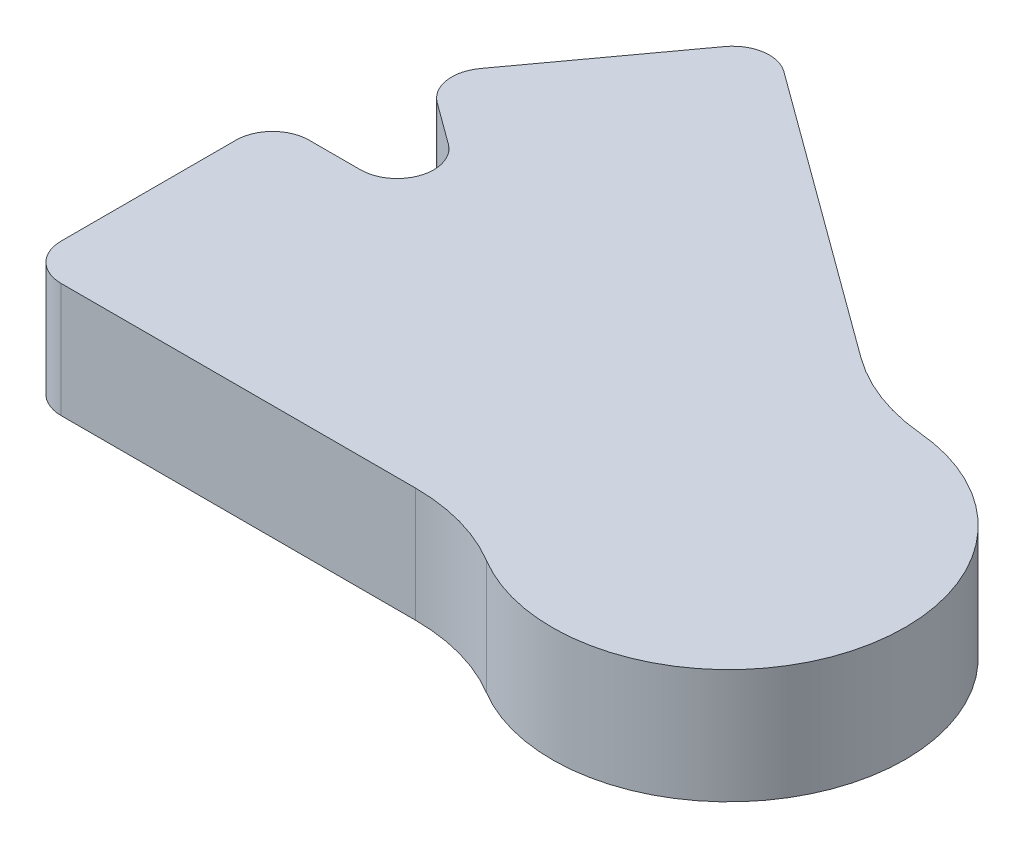
SolidWorks part; units mm, degrees
ref_plane "Front Plane" through (0, 0, 0) normal (0, 0, 1) x (1, 0, 0)
ref_plane "Top Plane" through (0, 0, 0) normal (0, 1, 0) x (1, 0, 0)
ref_plane "Right Plane" through (0, 0, 0) normal (1, 0, 0) x (0, 0, -1)
sketch "Sketch1" plane through (0, 0, 0) normal (0, 1, 0) x (1, 0, 0)
  line L0 (-43.2532, 22.6065) -> (-34.6727, 34.3467) construction
  line L1 (-42.5909, 18.3472) -> (-39.1434, 15.8276) construction
  line L2 (-45.212, 10.3187) -> (-40.9419, 10.3187) construction
  line L3 (-48.26, -7.2707) -> (-48.26, 7.2707) construction
  line L4 (-15.7343, -10.3187) -> (-45.212, -10.3187) construction
  line L5 (-30.4134, 35.009) -> (-6.6144, 17.6152) construction
  line L6 (-43.2532, 22.6065) -> (-34.6727, 34.3467)
  line L7 (-42.5909, 18.3472) -> (-39.1434, 15.8276)
  line L8 (-45.212, 10.3187) -> (-40.9419, 10.3187)
  line L9 (-48.26, -7.2707) -> (-48.26, 7.2707)
  line L10 (-15.7343, -10.3187) -> (-45.212, -10.3187)
  line L11 (-30.4134, 35.009) -> (-6.6144, 17.6152)
  arc A1 (-30.4134, 35.009) -> (-34.6727, 34.3467) centre (-32.2119, 32.5482) ccw construction
  arc A2 (-43.2532, 22.6065) -> (-42.5909, 18.3472) centre (-40.7923, 20.808) ccw construction
  arc A3 (-40.9419, 10.3187) -> (-39.1434, 15.8276) centre (-40.9419, 13.3667) ccw construction
  arc A4 (-45.212, 10.3187) -> (-48.26, 7.2707) centre (-45.212, 7.2707) ccw construction
  arc A5 (-48.26, -7.2707) -> (-45.212, -10.3187) centre (-45.212, -7.2707) ccw construction
  arc A6 (-7.5598, -12.5852) -> (-15.7343, -10.3187) centre (-15.7343, -26.1937) ccw construction
  circle A7 centre (0, 0) radius 14.6812 construction
  arc A8 (-6.6144, 17.6152) -> (1.3227, 14.6215) centre (2.7529, 30.4319) ccw construction
  arc A9 (-30.4134, 35.009) -> (-34.6727, 34.3467) centre (-32.2119, 32.5482) ccw
  arc A10 (-43.2532, 22.6065) -> (-42.5909, 18.3472) centre (-40.7923, 20.808) ccw
  arc A11 (-40.9419, 10.3187) -> (-39.1434, 15.8276) centre (-40.9419, 13.3667) ccw
  arc A12 (-45.212, 10.3187) -> (-48.26, 7.2707) centre (-45.212, 7.2707) ccw
  arc A13 (-48.26, -7.2707) -> (-45.212, -10.3187) centre (-45.212, -7.2707) ccw
  arc A14 (-7.5598, -12.5852) -> (-15.7343, -10.3187) centre (-15.7343, -26.1937) ccw
  arc A15 (-7.5598, -12.5852) -> (1.3227, 14.6215) centre (0, 0) ccw
  arc A16 (-6.6144, 17.6152) -> (1.3227, 14.6215) centre (2.7529, 30.4319) ccw
extrude "Boss-Extrude1" add sketch "Sketch1" against normal up to surface (9.525 mm away)
